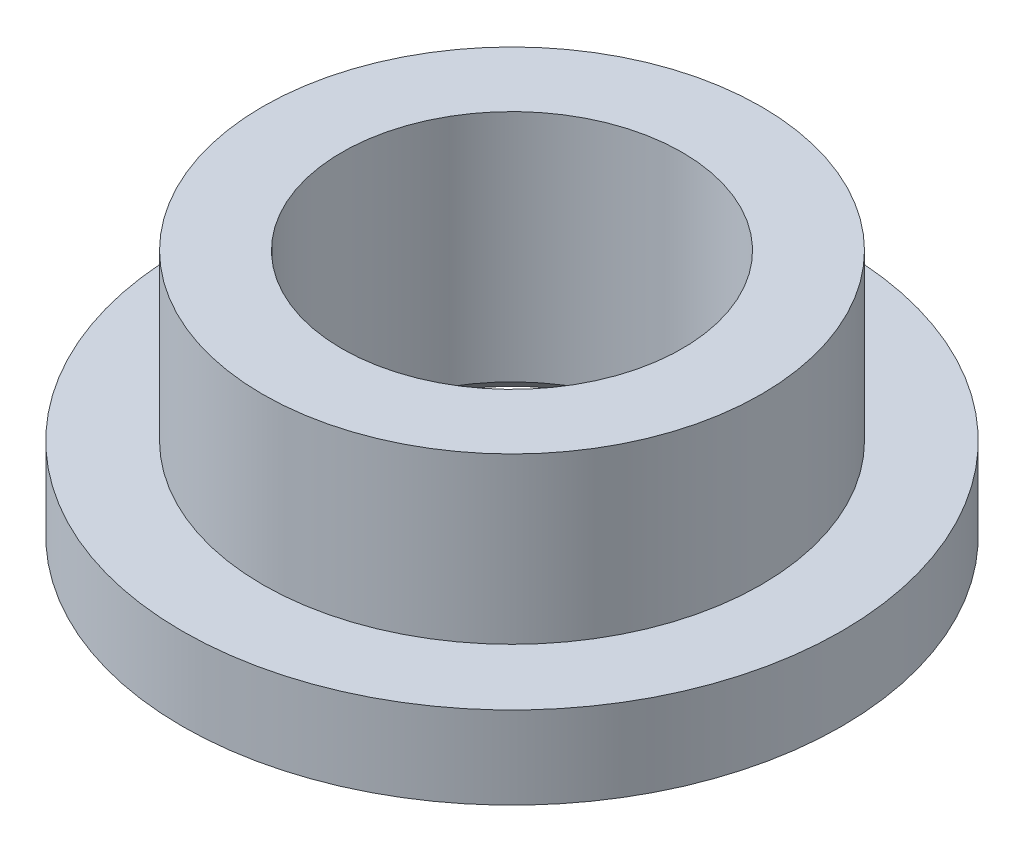
SolidWorks part; units mm, degrees
ref_plane "Front Plane" through (0, 0, 0) normal (0, 0, 1) x (1, 0, 0)
ref_plane "Top Plane" through (0, 0, 0) normal (0, 1, 0) x (1, 0, 0)
ref_plane "Right Plane" through (0, 0, 0) normal (1, 0, 0) x (0, 0, -1)
sketch "Sketch2" plane through (0, 0, 0) normal (0, 1, 0) x (1, 0, 0)
  circle A0 centre (0, 0) radius 4.8006
  dimension "D1" = 9.6012
extrude "Boss-Extrude1" add sketch "Sketch2" along normal blind 3.175
sketch "Sketch3" plane through (0, 0, 0) normal (0, -1, 0) x (-1, 0, 0)
  circle A0 centre (0, 0) radius 6.35
  dimension "D1" = 12.7
extrude "Boss-Extrude2" add sketch "Sketch3" along normal blind 1.5875
sketch "Sketch4" plane through (0, 3.175, 0) normal (0, 1, 0) x (1, 0, 0)
  circle A0 centre (0, 0) radius 3.2766
  dimension "D1" = 6.5532
extrude "Cut-Extrude1" cut sketch "Sketch4" against normal through all
chamfer "Chamfer1" distance 0.254 angle 45 1 edges at (0, -1.5875, 3.2766)
